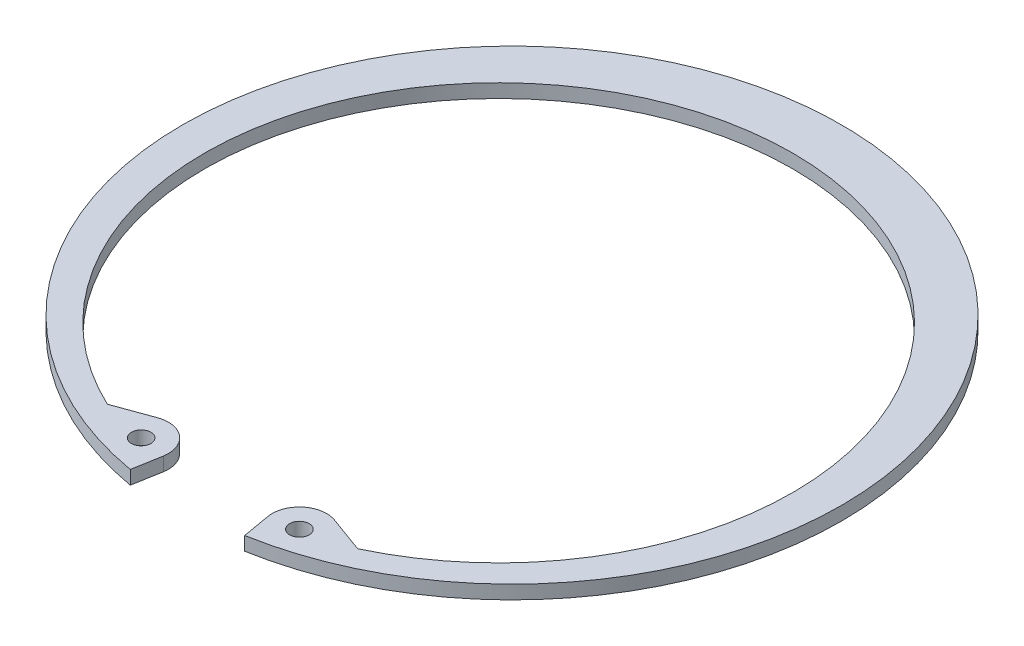
SolidWorks part; units mm, degrees
material "Cast Carbon Steel"
ref_plane "Front" through (0, 0, 0) normal (0, 0, 1) x (1, 0, 0)
ref_plane "Top" through (0, 0, 0) normal (0, 1, 0) x (1, 0, 0)
ref_plane "Right" through (0, 0, 0) normal (1, 0, 0) x (0, 0, -1)
sketch "Sketch2" plane through (0, 0, 0) normal (0, 1, 0) x (1, 0, 0)
  line L0 (0, 0) -> (0, -66.802) construction
  line L1 (-25.3672, -56.658) -> (-27.2978, -60.97) construction
  line L2 (11.6, -65.7871) -> (10.5974, -60.1008)
  line L3 (-11.6, -65.7871) -> (-10.5974, -60.1008)
  line L4 (0, 56.896) -> (0, 66.802) construction
  line L5 (25.3672, -56.658) -> (17.9275, -53.9502)
  line L6 (-25.3672, -56.658) -> (-17.9275, -53.9502)
  line L7 (14.5921, -53.8096) -> (-12.1752, -61.0683) construction
  line L8 (-12.1752, -61.0683) -> (-9.2834, -71.7321) construction
  line L9 (-9.2834, -71.7321) -> (17.4839, -64.4734) construction
  line L10 (14.5921, -53.8096) -> (17.4839, -64.4734) construction
  line L11 (16.038, -59.1415) -> (10.5974, -60.1008) construction
  line L12 (16.038, -59.1415) -> (17.4839, -64.4734) construction
  line L13 (14.5921, -53.8096) -> (-14.5921, -53.8096) construction
  line L14 (-14.5921, -53.8096) -> (-17.4839, -64.4734) construction
  line L15 (-66.802, 0) -> (66.802, 0) construction
  arc A1 (11.6, -65.7871) -> (-11.6, -65.7871) centre (0, 0) ccw
  arc A2 (25.3672, -56.658) -> (-25.3672, -56.658) centre (0, -2.7145) ccw
  circle A3 centre (0, 0) radius 66.802 construction
  arc A4 (10.5974, -60.1008) -> (17.9275, -53.9502) centre (16.038, -59.1415) cw
  arc A5 (-10.5974, -60.1008) -> (-17.9275, -53.9502) centre (-16.038, -59.1415) ccw
  circle A6 centre (16.038, -59.1415) radius 1.9812
  circle A7 centre (-16.038, -59.1415) radius 1.9812
  arc A8 (25.3672, -56.658) -> (-25.3672, -56.658) centre (0, -2.7145) cw construction
  circle A9 centre (0, 0) radius 55.118 construction
  point P5 (16.038, -59.1415)
  point P10 (14.5921, -53.8096)
  dimension "D1" = 60
  dimension "D2" = 60
  dimension "L" = 110.236
  dimension "R" = 3.9624
  dimension "Df" = 133.604
  dimension "H" = 11.049
  dimension "Angle" = 10
  dimension "Sec. Max" = 9.906
  dimension "Sec. Min" = 4.7244
extrude "Extrude1" add sketch "Sketch2" against normal blind 2.7686
fillet "Fillet1" radius 0.254 2 edges at (-25.3672, -1.3843, 56.658) (25.3672, -1.3843, 56.658)
sketch "Sketch3" plane through (0, 0, 0) normal (1, 0, 0) x (0, 0, -1)
  line L0 (-63.5, -28.9306) -> (-63.5, -2.9083)
  line L1 (-63.5, -2.9083) -> (-66.802, -2.9083)
  line L2 (-66.802, -2.9083) -> (-66.802, 0.1397)
  line L3 (-66.802, 0.1397) -> (-63.5, 0.1397)
  line L4 (-63.5, 0.1397) -> (-63.5, 4.2926)
  line L5 (-63.5, -28.9306) -> (-70.104, -28.9306)
  line L6 (-63.5, -2.9083) -> (0, -2.9083) construction
  line L7 (-63.5, 4.2926) -> (-70.104, 4.2926)
  line L8 (0, 130.3401) -> (0, 164.6301) construction
  line L9 (0, -2.9083) -> (0, 0.1397) construction
  line L10 (0, 0.1397) -> (-63.5, 0.1397) construction
  line L11 (-66.802, -1.3843) -> (0, -1.3843) construction
  line L12 (0, -135.0899) -> (0, 130.3401) construction
  line L13 (-56.6128, -2.7686) -> (56.896, -2.7686) construction
  line L14 (-70.104, -28.9306) -> (-70.104, 4.2926)
  dimension "Shaft Lg" = 33.2232
  dimension "D1" = 1.3843
  dimension "D2" = 3.302
  dimension "D4" = 3.302
  dimension "D3" = 4.1529
revolve "Revolve1" [suppressed] add sketch "Sketch3" angle 360 about L8
delete or keep bodies "Body-Delete1" [suppressed] type delete bodies bodies 116
equation "\"D3@Sketch3\" = \"Shaft Lg@Sketch3\"/8"
equation "\"Shaft Lg@Sketch3\" = \"D1@Extrude1\"*12"
equation "\"D1@Sketch3\" = \"D1@Extrude1\"/2"
equation "\"D2@Sketch3\" = \"D4@Sketch3\""
